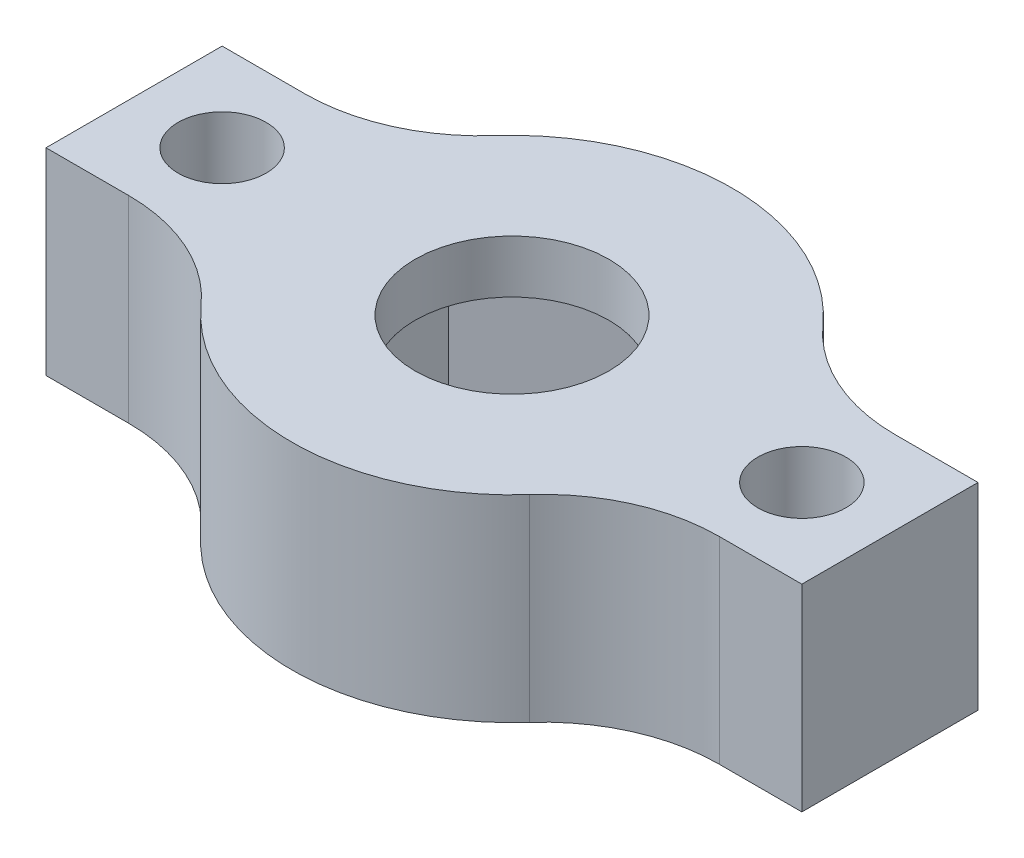
SolidWorks part; units mm, degrees
ref_plane "Спереди" through (0, 0, 0) normal (0, 0, 1) x (1, 0, 0)
ref_plane "Сверху" through (0, 0, 0) normal (0, 1, 0) x (1, 0, 0)
ref_plane "Справа" through (0, 0, 0) normal (1, 0, 0) x (0, 0, -1)
sketch "Эскиз1" plane through (0, 0, 0) normal (0, 1, 0) x (1, 0, 0)
  line L1 (8.5, -4.9075) -> (8.5, 4.9075)
  line L2 (8.5, 4.9075) -> (0, 9.815)
  line L3 (0, 9.815) -> (-8.5, 4.9075)
  line L4 (-8.5, 4.9075) -> (-8.5, -4.9075)
  line L5 (-8.5, -4.9075) -> (0, -9.815)
  line L6 (0, -9.815) -> (8.5, -4.9075)
  circle A0 centre (0, 0) radius 8.5 construction
  circle A1 centre (0, 0) radius 8.5 construction
  circle A2 centre (0, 0) radius 12.5
  dimension "D1" = 17
  dimension "D2" = 25
extrude "Вытянуть1" add sketch "Эскиз1" along normal blind 8.2
sketch "Эскиз2" plane through (0, 8.2, 0) normal (0, 1, 0) x (1, 0, 0)
  circle A0 centre (0, 0) radius 12.5
  circle A1 centre (0, 0) radius 12.5 construction
extrude "Вытянуть2" add sketch "Эскиз2" along normal blind 3
sketch "Эскиз3" plane through (0, 0, 0) normal (0, -1, 0) x (1, 0, 0)
  line L0 (0, 9.815) -> (0, -9.815) construction
  line L1 (11.4564, 5) -> (21.4564, 5)
  line L2 (11.4564, 5) -> (11.4564, -5)
  line L3 (11.4564, -5) -> (21.4564, -5)
  line L4 (21.4564, 5) -> (21.4564, -5)
  line L5 (-21.4564, 5) -> (-21.4564, -5)
  line L6 (-11.4564, -5) -> (-21.4564, -5)
  line L7 (-11.4564, 5) -> (-11.4564, -5)
  line L8 (-11.4564, 5) -> (-21.4564, 5)
  circle A0 centre (0, 0) radius 12.5 construction
  dimension "D1" = 10
  dimension "D2" = 10
extrude "Вытянуть3" add sketch "Эскиз3" against normal up to surface (11.2 mm away) up to face at (0, 11.2, 12.5)
fillet "Скругление1" radius 10 4 edges at (11.4564, 5.6, -5) (-11.4564, 5.6, -5) (-11.4564, 5.6, 5) (11.4564, 5.6, 5)
sketch "Эскиз4" plane through (0, 11.2, 0) normal (0, 1, 0) x (1, 0, 0)
  line L0 (-21.4564, -5) -> (-21.4564, 5) construction
  line L1 (21.4564, 5) -> (21.4564, -5) construction
  circle A0 centre (16.4564, 0) radius 2.5
  circle A1 centre (-16.4564, 0) radius 2.5
  dimension "D1" = 5
  dimension "D2" = 5
  dimension "D3" = 5
  dimension "D4" = 5
extrude "Вытянуть4" cut sketch "Эскиз4" against normal through all
sketch "Эскиз5" plane through (0, 11.2, 0) normal (0, 1, 0) x (1, 0, 0)
  circle A0 centre (0, 0) radius 5.5
  dimension "D1" = 11
extrude "Вытянуть5" cut sketch "Эскиз5" against normal blind 4
